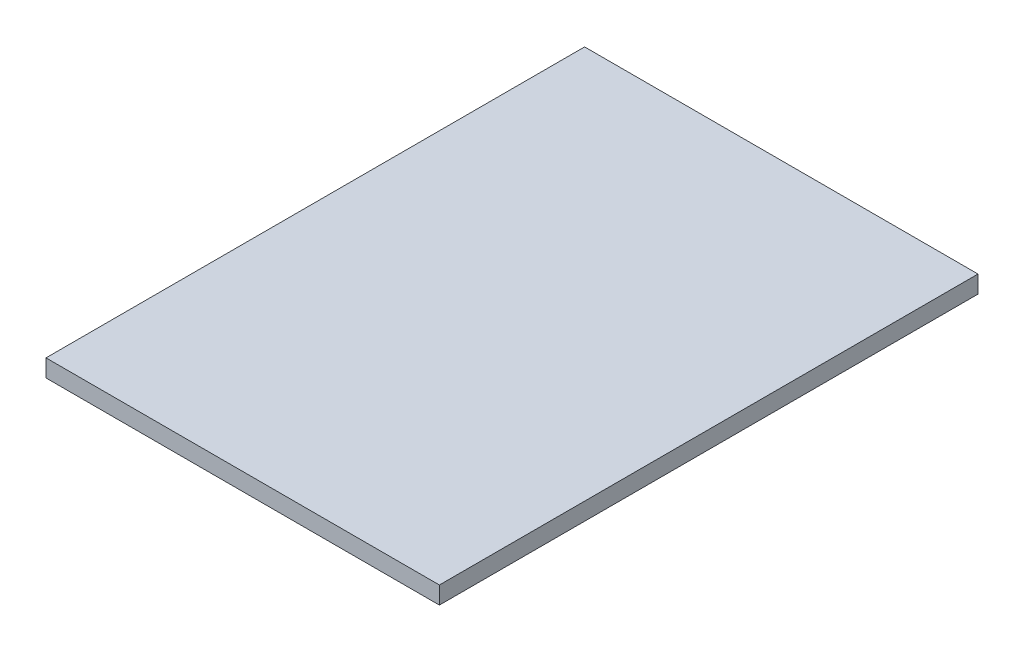
SolidWorks part; units mm, degrees
ref_plane "Front Plane" through (0, 0, 0) normal (0, 0, 1) x (1, 0, 0)
ref_plane "Top Plane" through (0, 0, 0) normal (0, 1, 0) x (1, 0, 0)
ref_plane "Right Plane" through (0, 0, 0) normal (1, 0, 0) x (0, 0, -1)
sketch "Sketch1" plane through (0, 0, 0) normal (0, 1, 0) x (1, 0, 0)
  line L1 (0, 0) -> (679.45, 0)
  line L2 (0, 0) -> (0, 930.275)
  line L3 (0, 930.275) -> (679.45, 930.275)
  line L4 (679.45, 0) -> (679.45, 930.275)
  dimension "D1" = 930.275
  dimension "D2" = 679.45
extrude "Boss-Extrude1" add sketch "Sketch1" along normal blind 30.099
sketch "Sketch2" plane through (0, 0, 0) normal (0, -1, 0) x (1, 0, 0)
  line L0 (6.096, -6.096) -> (6.096, -924.179)
  line L1 (6.096, -924.179) -> (673.354, -924.179)
  line L2 (673.354, -924.179) -> (673.354, -6.096)
  line L3 (673.354, -6.096) -> (6.096, -6.096)
  line L4 (0, 0) -> (0, -930.275)
  line L5 (0, -930.275) -> (679.45, -930.275)
  line L6 (679.45, -930.275) -> (679.45, 0)
  line L7 (679.45, 0) -> (0, 0)
  line L8 (0, 0) -> (0, -930.275) construction
  line L9 (0, -930.275) -> (679.45, -930.275) construction
  line L10 (679.45, -930.275) -> (679.45, 0) construction
  line L11 (679.45, 0) -> (0, 0) construction
  dimension "D1" = 0
  dimension "D2" = 6.096
extrude "Cut-Extrude1" cut sketch "Sketch2" against normal blind 23.876
sketch "Sketch3" plane through (0, 0, 0) normal (0, -1, 0) x (1, 0, 0)
  line L1 (654.558, -24.892) -> (24.892, -24.892)
  line L2 (654.558, -24.892) -> (654.558, -905.383)
  line L3 (654.558, -905.383) -> (24.892, -905.383)
  line L4 (0, 0) -> (0, -930.275)
  line L5 (0, -930.275) -> (679.45, -930.275)
  line L6 (679.45, -930.275) -> (679.45, 0)
  line L7 (679.45, 0) -> (0, 0)
  line L8 (0, 0) -> (0, -930.275)
  line L9 (0, -930.275) -> (679.45, -930.275)
  line L10 (679.45, -930.275) -> (679.45, 0)
  line L11 (679.45, 0) -> (0, 0)
  line L12 (24.892, -24.892) -> (24.892, -905.383)
  dimension "D2" = 24.892
  dimension "D3" = 24.892
  dimension "D4" = 24.892
  dimension "D5" = 24.892
  dimension "D1" = 0
extrude "Boss-Extrude2" add sketch "Sketch3" against normal blind 0.889
sketch "Sketch4" plane through (0, 23.876, 0) normal (0, -1, 0) x (1, 0, 0)
  line L0 (679.45, -930.275) -> (0, -930.275) construction
  line L1 (396.875, -790.575) -> (282.575, -790.575)
  line L2 (396.875, -790.575) -> (396.875, -866.775)
  line L3 (396.875, -866.775) -> (282.575, -866.775)
  line L4 (282.575, -790.575) -> (282.575, -866.775)
  point P6 (339.725, -930.275)
  point P7 (339.725, -866.775)
  point P8 (282.575, -828.675)
  dimension "D1" = 114.3
  dimension "D2" = 76.2
  dimension "D3" = 101.6
extrude "Boss-Extrude3" add sketch "Sketch4" along normal blind 12.7
